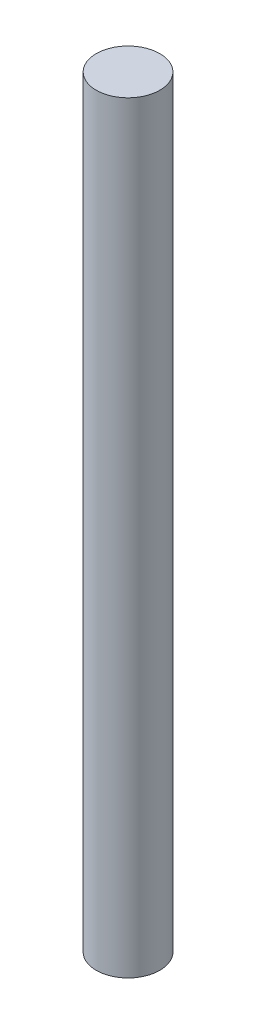
SolidWorks part; units mm, degrees
material "AISI 1010 Steel, hot rolled bar"
ref_plane "Front Plane" through (0, 0, 0) normal (0, 0, 1) x (1, 0, 0)
ref_plane "Top Plane" through (0, 0, 0) normal (0, 1, 0) x (1, 0, 0)
ref_plane "Right Plane" through (0, 0, 0) normal (1, 0, 0) x (0, 0, -1)
sketch "Sketch1" plane through (0, 0, 0) normal (0, 1, 0) x (1, 0, 0)
  circle A0 centre (0, 0) radius 3.175
  dimension "D1" = 6.35
extrude "Boss-Extrude1" add sketch "Sketch1" along normal blind 76.2
equation "\"3.7o\"=3.75"
